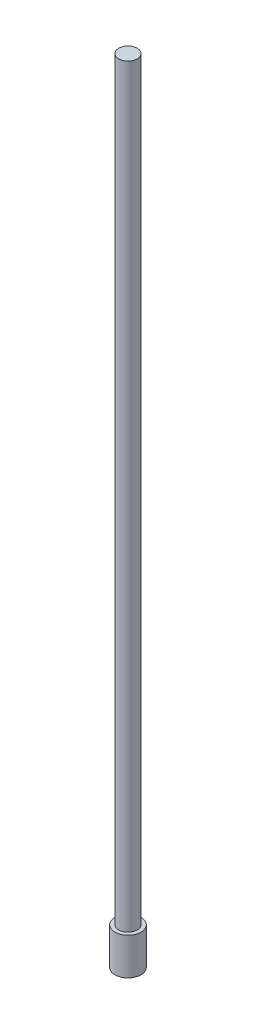
SolidWorks part; units mm, degrees
ref_plane "Front Plane" through (0, 0, 0) normal (0, 0, 1) x (1, 0, 0)
ref_plane "Top Plane" through (0, 0, 0) normal (0, 1, 0) x (1, 0, 0)
ref_plane "Right Plane" through (0, 0, 0) normal (1, 0, 0) x (0, 0, -1)
sketch "Sketch1" plane through (0, 0, 0) normal (0, 1, 0) x (1, 0, 0)
  circle A0 centre (0, 0) radius 3.5
  circle A1 centre (0, 0) radius 2.5
  dimension "D1" = 7
  dimension "D2" = 5
extrude "Boss-Extrude1" add sketch "Sketch1" along normal blind 10
sketch "Sketch2" plane through (0, 10, 0) normal (0, 1, 0) x (1, 0, 0)
  circle A4 centre (0, 0) radius 2.5 construction
  circle A5 centre (0, 0) radius 2.5
extrude "Boss-Extrude2" add sketch "Sketch2" along normal mid plane 7.5
sketch "Sketch3" plane through (0, 13.75, 0) normal (0, 1, 0) x (1, 0, 0)
  circle A2 centre (0, 0) radius 2.5
  circle A3 centre (0, 0) radius 2.5
  dimension "D1" = 0
extrude "Boss-Extrude3" add sketch "Sketch3" along normal blind 200
